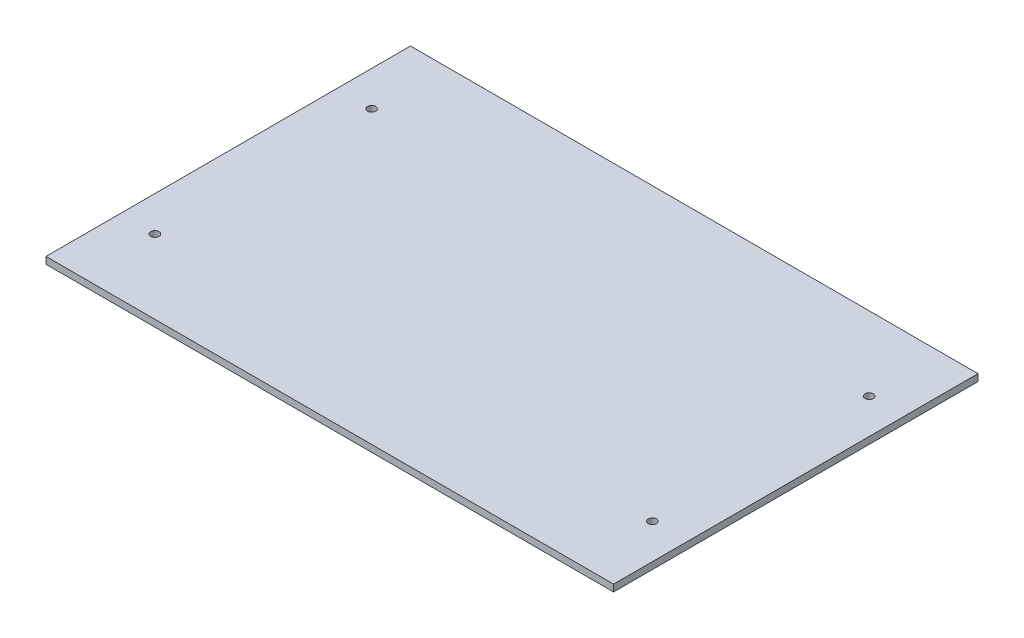
SolidWorks part; units mm, degrees
material "ABS PC"
ref_plane "Front Plane" through (0, 0, 0) normal (0, 0, 1) x (1, 0, 0)
ref_plane "Top Plane" through (0, 0, 0) normal (0, 1, 0) x (1, 0, 0)
ref_plane "Right Plane" through (0, 0, 0) normal (1, 0, 0) x (0, 0, -1)
sketch "Sketch1" plane through (0, 0, 0) normal (0, 1, 0) x (1, 0, 0)
  line L0 (231.775, 297.688) -> (231.775, 0) construction
  line L1 (0, 0) -> (463.55, 0)
  line L2 (0, 0) -> (0, 297.688)
  line L3 (0, 297.688) -> (463.55, 297.688)
  line L4 (463.55, 0) -> (463.55, 297.688)
  line L5 (28.575, 60.325) -> (28.575, 237.363) construction
  line L6 (28.575, 237.363) -> (28.575, 414.401) construction
  line L7 (434.975, 237.363) -> (434.975, 414.401) construction
  line L8 (434.975, 60.325) -> (434.975, 237.363) construction
  circle A0 centre (28.575, 60.325) radius 3.3782
  circle A1 centre (28.575, 237.363) radius 3.3782
  circle A4 centre (434.975, 237.363) radius 3.3782
  circle A5 centre (434.975, 60.325) radius 3.3782
  dimension "D3" = 6.7564
  dimension "D1" = 463.55
  dimension "D2" = 60.325
  dimension "D4" = 60.325
  dimension "D5" = 28.575
  dimension "D6" = 177.038
extrude "Boss-Extrude1" add sketch "Sketch1" along normal blind 5.588
fillet "Fillet1" [suppressed] radius 3.175
